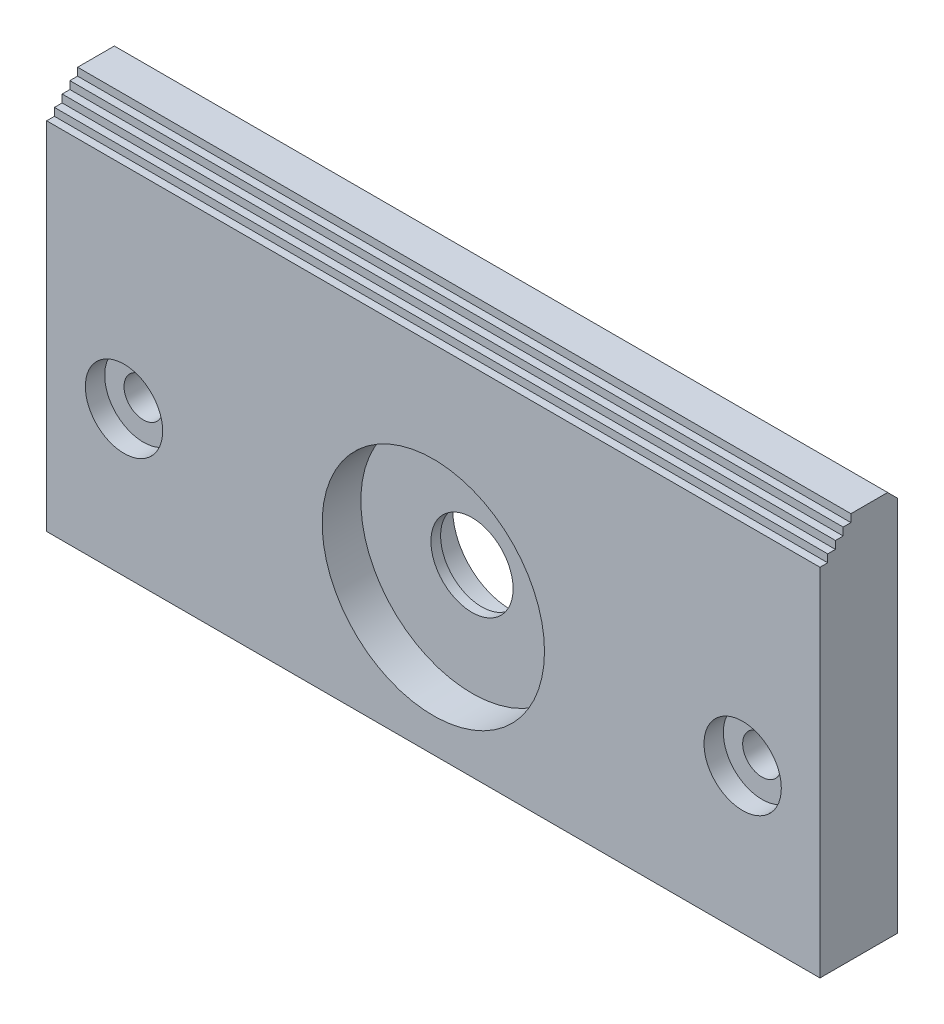
SolidWorks part; units mm, degrees
ref_plane "前视基准面" through (0, 0, 0) normal (0, 0, 1) x (1, 0, 0)
ref_plane "上视基准面" through (0, 0, 0) normal (0, 1, 0) x (1, 0, 0)
ref_plane "右视基准面" through (0, 0, 0) normal (1, 0, 0) x (0, 0, -1)
other "Configuration Table"
ref_plane "基准面1" through (0, 0, 8) normal (0, 0, 1) x (1, 0, 0)
sketch "草图1" plane through (0, 0, 8) normal (0, 0, 1) x (1, 0, 0)
  line L0 (80, -19.1667) -> (80, 40.8333)
  line L1 (80, 40.8333) -> (0, 40.8333)
  line L2 (0, 40.8333) -> (0, -19.1667)
  line L3 (0, -19.1667) -> (80, -19.1667)
  dimension "D1" = 80
  dimension "D2" = 60
extrude "凸台-拉伸1" add sketch "草图1" against normal blind 8
hole_wizard "M3.5 六角头机械螺钉的柱形沉头孔1" positions "草图13" profile "草图12" counterbore size "M3.5" standard "ANSI Metric" end condition through all
sketch "草图13" plane through (0, 0, 8) normal (0, 0, 1) x (1, 0, 0)
  line L1 (0, 15.8333) -> (80, 15.8333) construction
  line L2 (0, 40.8333) -> (0, -19.1667) construction
  line L3 (80, -19.1667) -> (80, 40.8333) construction
  line L4 (80, 40.8333) -> (0, 40.8333) construction
  point P0 (8, 15.8333)
  point P1 (72, 15.8333)
  point P13 (0, 0)
  point P14 (0, 0)
  dimension "D1" = 8
  dimension "D2" = 8
  dimension "D3" = 25
sketch "草图12" plane through (8, 15.8333, 8) normal (1, 0, 0) x (0, -1, 0)
  line L0 (0, 0) -> (0, 8)
  line L1 (0, 8) -> (2, 8)
  line L3 (2, 8) -> (2, 2)
  line L4 (2, 2) -> (4, 2)
  line L5 (4, 2) -> (4, 0)
  line L7 (4, 0) -> (0, 0)
  line L11 (0, -6.35) -> (0, 107.95) construction
  dimension "通孔孔直径" = 4
  dimension "通孔孔深度" = 8
  dimension "柱形沉头孔直径" = 8
  dimension "柱形沉头孔深度" = 2
sketch "草图14" plane through (0, 0, 8) normal (0, 0, 1) x (1, 0, 0)
  line L0 (40, 40.8333) -> (40, -19.1667) construction
  line L1 (80, 40.8333) -> (0, 40.8333) construction
  line L2 (0, -19.1667) -> (80, -19.1667) construction
  line L3 (0, 40.8333) -> (0, -19.1667) construction
  line L4 (0, 38.8333) -> (80, 38.8333)
  line L5 (0, 38.8333) -> (0, 36.8333)
  line L6 (0, 36.8333) -> (80, 36.8333)
  line L7 (40, 38.8333) -> (40, 36.8333)
  line L8 (80, -19.1667) -> (80, 40.8333) construction
  line L9 (15, 40.8333) -> (31, 24.8333)
  line L10 (6, 40.8333) -> (8, 40.8333)
  line L11 (6, 40.8333) -> (6, 24.8333)
  line L12 (6, 24.8333) -> (8, 24.8333)
  line L13 (8, 40.8333) -> (8, 24.8333)
  line L18 (39, 40.8333) -> (41, 40.8333)
  line L19 (39, 40.8333) -> (39, 24.8333)
  line L20 (39, 24.8333) -> (41, 24.8333)
  line L21 (40, 40.8333) -> (40, 24.8333)
  line L22 (31, 24.8333) -> (32.4142, 26.2475)
  line L23 (32.4142, 26.2475) -> (16.4142, 42.2475)
  line L24 (16.4142, 42.2475) -> (15, 40.8333)
  line L25 (0, 24.8333) -> (80, 24.8333) construction
  line L26 (74, 24.8333) -> (72, 24.8333)
  line L27 (72, 40.8333) -> (72, 24.8333)
  line L28 (74, 40.8333) -> (72, 40.8333)
  line L29 (74, 40.8333) -> (74, 24.8333)
  line L30 (47.5858, 26.2475) -> (63.5858, 42.2475)
  line L31 (49, 24.8333) -> (47.5858, 26.2475)
  line L32 (65, 40.8333) -> (49, 24.8333)
  line L33 (63.5858, 42.2475) -> (65, 40.8333)
  line L34 (41, 40.8333) -> (41, 24.8333)
  line L35 (80, 38.8333) -> (80, 36.8333)
  dimension "D1" = 2
  dimension "D2" = 2
  dimension "D3" = 6
  dimension "D4" = 2
  dimension "D5" = 16
  dimension "D6" = 2
  dimension "D7" = 1
  dimension "D8" = 7
  dimension "D9" = 45
extrude "切除-拉伸1" cut sketch "草图14" against normal blind 1 contours L4 L35 L6 L5 | L13 L12 L11 L10 | L9 L22 L23 L24 | L19 L20 L34 L18 | L30 L33 L32 L31 | L27 L26 L29 L28
sketch "草图15" plane through (0, 0, 8) normal (0, 0, 1) x (1, 0, 0)
  line L0 (40, 40.8333) -> (40, -19.1667) construction
  line L1 (39, 40.8333) -> (41, 40.8333) construction
  line L2 (0, -19.1667) -> (80, -19.1667) construction
  line L3 (39, 40.8333) -> (17.8284, 40.8333) construction
  circle A0 centre (40, 15.8333) radius 4.25
  point P8 (0, 0)
  point P10 (0, 0)
  point P11 (0, 0)
  point P14 (0, 0)
  point P16 (39.8318, 10.5025)
  point P17 (34.4019, 11.7929)
  dimension "D1" = 8.5
  dimension "D2" = 25
extrude "切除-拉伸2" cut sketch "草图15" against normal up to next
sketch "草图17" plane through (0, 0, 8) normal (0, 0, 1) x (1, 0, 0)
  circle A0 centre (40, 15.8333) radius 11.5
  dimension "D1" = 23
extrude "切除-拉伸4" cut sketch "草图17" against normal blind 4
sketch "草图18" plane through (0, 0, 0) normal (0, 0, -1) x (-1, 0, 0)
  circle A0 centre (-40, 15.8333) radius 6
  dimension "D1" = 12
extrude "切除-拉伸5" cut sketch "草图18" against normal blind 3
chamfer "倒角1" distance 1.5 angle 45 2 edges at (74, 15.8333, 0) (10, 15.8333, 0)
chamfer "倒角2" distance 1 angle 45 1 edges at (40, 40.8333, 0)
sketch "草图20" plane through (0, 0, 8) normal (0, 0, 1) x (1, 0, 0)
  line L0 (80, -19.1667) -> (80, 36.8333) construction
  line L1 (0, -19.1667) -> (80, -19.1667)
  line L2 (0, -19.1667) -> (0, -13.1667)
  line L3 (0, -13.1667) -> (80, -13.1667)
  line L4 (80, -19.1667) -> (80, -13.1667)
  dimension "D1" = 6
extrude "切除-拉伸6" cut sketch "草图20" against normal blind 1
sketch "草图21" plane through (0, 0, 7) normal (0, 0, 1) x (1, 0, 0)
  line L0 (80, -19.1667) -> (80, -13.1667) construction
  line L1 (0, -19.1667) -> (80, -19.1667)
  line L2 (0, -19.1667) -> (0, -15.1667)
  line L3 (0, -15.1667) -> (80, -15.1667)
  line L4 (80, -19.1667) -> (80, -15.1667)
  dimension "D1" = 4
extrude "切除-拉伸7" cut sketch "草图21" against normal blind 1
sketch "草图22" plane through (0, 0, 6) normal (0, 0, 1) x (1, 0, 0)
  line L1 (0, -19.1667) -> (80, -19.1667)
  line L2 (0, -19.1667) -> (0, -17.1667)
  line L3 (0, -17.1667) -> (80, -17.1667)
  line L4 (80, -19.1667) -> (80, -17.1667)
  dimension "D1" = 2
extrude "切除-拉伸8" cut sketch "草图22" against normal blind 1
sketch "草图23" plane through (0, 0, 8) normal (0, 0, 1) x (1, 0, 0)
  line L0 (6, 24.8333) -> (8, 24.8333) construction
  line L1 (31, 24.8333) -> (32.4142, 26.2475) construction
  line L3 (49, 24.8333) -> (47.5858, 26.2475) construction
  line L4 (74, 24.8333) -> (72, 24.8333) construction
  circle A0 centre (7, 24.8333) radius 1
  circle A1 centre (31.7071, 25.5404) radius 1
  circle A3 centre (48.2929, 25.5404) radius 1
  circle A4 centre (73, 24.8333) radius 1
  point P25 (40, 24.8333)
extrude "切除-拉伸9" cut sketch "草图23" against normal up to surface (1 mm away) up to face at (40, 35.7375, 7)
sketch "草图24" plane through (0, 0, 8) normal (0, 0, 1) x (1, 0, 0)
  line L0 (0, 36.8333) -> (0, -13.1667) construction
  line L1 (0, 0.8333) -> (80, 0.8333)
  line L2 (0, 0.8333) -> (0, -19.1667)
  line L3 (0, -19.1667) -> (80, -19.1667)
  line L4 (80, 0.8333) -> (80, -19.1667)
  dimension "D1" = 20
extrude "切除-拉伸10" cut sketch "草图24" against normal up to next
sketch "草图25" plane through (0, 0, 8) normal (0, 0, 1) x (1, 0, 0)
  line L0 (80, 0.8333) -> (80, 36.8333) construction
  line L1 (0, 40.8333) -> (80, 40.8333)
  line L2 (0, 40.8333) -> (0, 22.8333)
  line L3 (0, 22.8333) -> (30.8759, 22.8333)
  line L4 (80, 40.8333) -> (80, 22.8333)
  line L5 (0, 36.8333) -> (0, 0.8333) construction
  line L6 (49.1241, 22.8333) -> (80, 22.8333)
  arc A0 (49.1241, 22.8333) -> (30.8759, 22.8333) centre (40, 15.8333) ccw
  dimension "D1" = 18
extrude "凸台-拉伸2" add sketch "草图25" against normal blind 3
sketch "草图26" plane through (0, 0, 0) normal (-1, 0, 0) x (0, 0, 1)
  line L0 (4.8, 40.8333) -> (4.8, 40.0333)
  line L1 (1, 40.8333) -> (8, 40.8333) construction
  line L2 (4.8, 40.0333) -> (5.6, 40.0333)
  line L3 (5.6, 40.0333) -> (5.6, 39.2333)
  line L4 (5.6, 39.2333) -> (6.4, 39.2333)
  line L5 (6.4, 39.2333) -> (6.4, 38.4333)
  line L6 (6.4, 38.4333) -> (7.2, 38.4333)
  line L7 (7.2, 38.4333) -> (7.2, 37.6333)
  line L8 (7.2, 37.6333) -> (8, 37.6333)
  line L9 (8, 40.8333) -> (8, 0.8333) construction
  line L10 (8, 37.6333) -> (8, 40.8333)
  line L11 (8, 40.8333) -> (4.8, 40.8333)
  dimension "D1" = 0.8
  dimension "D2" = 0.8
  dimension "D3" = 0.8
  dimension "D4" = 0.8
  dimension "D5" = 0.8
  dimension "D6" = 0.8
  dimension "D7" = 0.8
  dimension "D8" = 0.8
extrude "切除-拉伸11" cut sketch "草图26" against normal up to next
